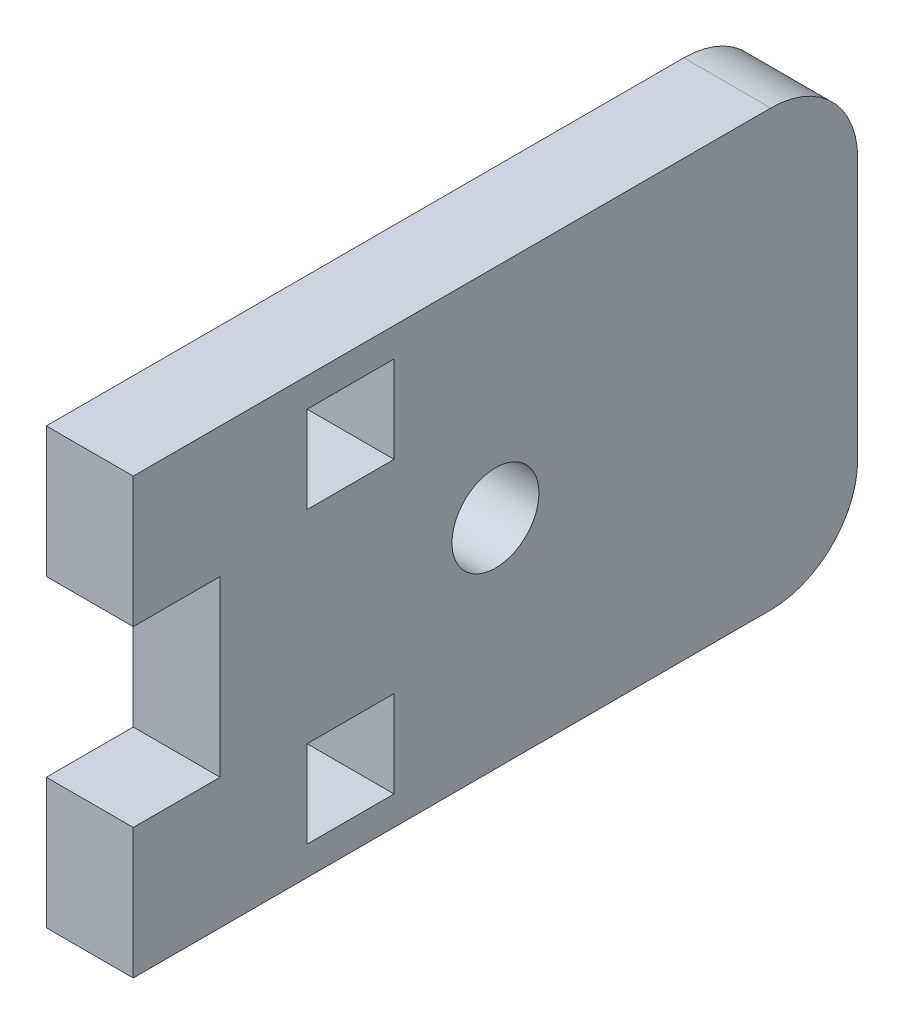
SolidWorks part; units mm, degrees
ref_plane "Front Plane" through (0, 0, 0) normal (0, 0, 1) x (1, 0, 0)
ref_plane "Top Plane" through (0, 0, 0) normal (0, 1, 0) x (1, 0, 0)
ref_plane "Right Plane" through (0, 0, 0) normal (1, 0, 0) x (0, 0, -1)
sketch "Sketch1" plane through (0, 0, 0) normal (1, 0, 0) x (0, 0, -1)
  line L0 (-12.5, -7.5) -> (-12.5, -3)
  line L1 (-12.5, 7.5) -> (12.5, 7.5)
  line L2 (-12.5, -3) -> (-9.5, -3)
  line L3 (-12.5, -7.5) -> (12.5, -7.5)
  line L4 (12.5, 7.5) -> (12.5, -7.5)
  line L5 (-9.5, -3) -> (-9.5, 3)
  line L6 (-9.5, 3) -> (-12.5, 3)
  line L7 (-12.5, 3) -> (-12.5, 7.5)
  circle A0 centre (0, 0) radius 1.5
  point P0 (0, 0)
  dimension "D7" = 3
  dimension "D1" = 15
  dimension "D2" = 25
  dimension "D3" = 3
  dimension "D4" = 4.5
  dimension "D5" = 4.5
  dimension "D6" = 12.5
extrude "Boss-Extrude1" add sketch "Sketch1" along normal blind 3
sketch "Sketch2" plane through (3, 0, 0) normal (1, 0, 0) x (0, 0, -1)
  line L0 (-6.5, 9.7574) -> (-6.5, -9.5816) construction
  line L1 (-9.5, 3) -> (-9.5, -3) construction
  line L2 (-6.5, 6.5) -> (-6.5, 3.5)
  line L3 (-6.5, 6.5) -> (-3.5, 6.5)
  line L4 (-6.5, 3.5) -> (-3.5, 3.5)
  line L5 (-3.5, 6.5) -> (-3.5, 3.5)
  line L6 (-6.5, -3.5) -> (-6.5, -6.5)
  line L7 (-6.5, -3.5) -> (-3.5, -3.5)
  line L8 (-6.5, -6.5) -> (-3.5, -6.5)
  line L9 (-3.5, -3.5) -> (-3.5, -6.5)
  point P4 (-3.5, 5)
  point P11 (-9.5, 0)
  point P14 (-3.5, -5)
  dimension "D1" = 3
  dimension "D2" = 3
  dimension "D3" = 3
  dimension "D4" = 3
  dimension "D5" = 3
  dimension "D6" = 5
  dimension "D7" = 5
extrude "Cut-Extrude1" cut sketch "Sketch2" against normal blind 3
fillet "Fillet1" radius 3 2 edges at (1.5, -7.5, -12.5) (1.5, 7.5, -12.5)
